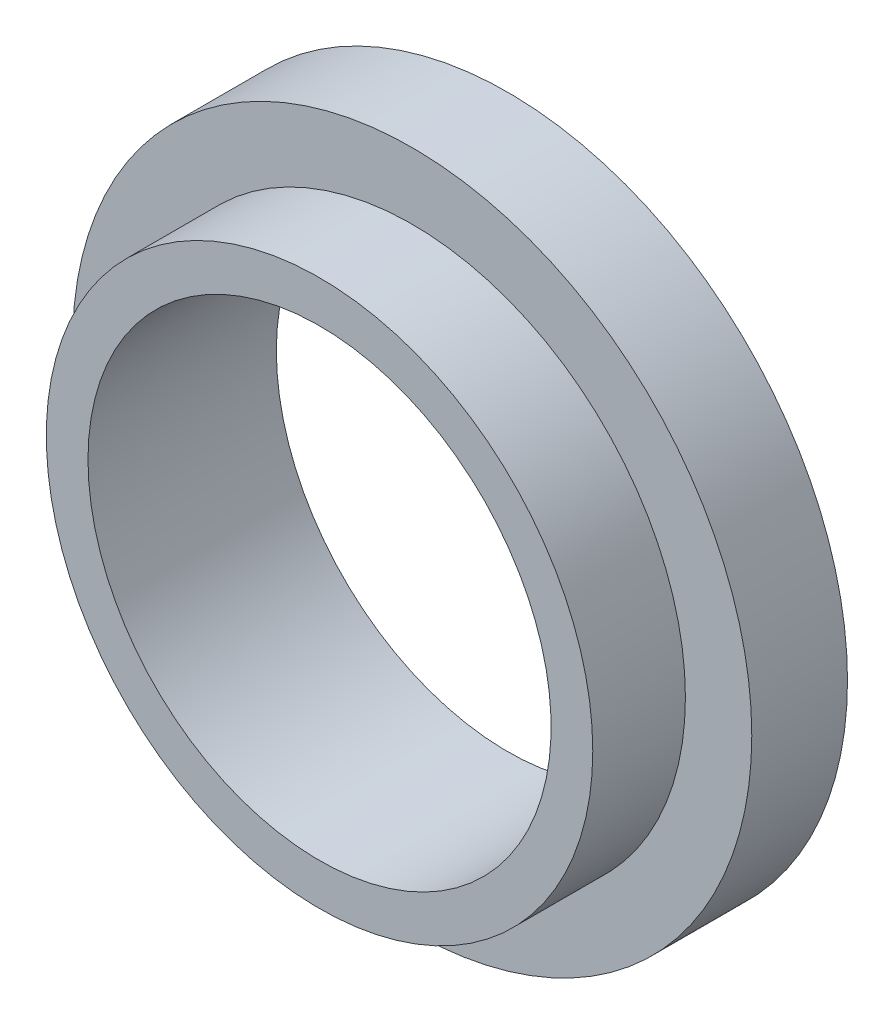
SolidWorks part; units mm, degrees
material "Phosphor bronze 10% D, UNS C52400"
ref_plane "Front Plane" through (0, 0, 0) normal (0, 0, 1) x (1, 0, 0)
ref_plane "Top Plane" through (0, 0, 0) normal (0, 1, 0) x (1, 0, 0)
ref_plane "Right Plane" through (0, 0, 0) normal (1, 0, 0) x (0, 0, -1)
sketch "Sketch1" plane through (0, 0, 0) normal (0, 0, 1) x (1, 0, 0)
  circle A0 centre (0, 0) radius 55
  dimension "D1" = 110
extrude "Boss-Extrude1" add sketch "Sketch1" along normal blind 15.5
sketch "Sketch2" plane through (0, 0, 15.5) normal (0, 0, 1) x (1, 0, 0)
  circle A0 centre (0, 0) radius 44.25
  dimension "D1" = 88.5
extrude "Boss-Extrude2" add sketch "Sketch2" along normal blind 15
sketch "Sketch3" plane through (0, 0, 0) normal (0, 0, -1) x (-1, 0, 0)
  circle A0 centre (0, 0) radius 37.5
  dimension "D1" = 75
extrude "Cut-Extrude3" cut sketch "Sketch3" against normal through all both and the other way through all
